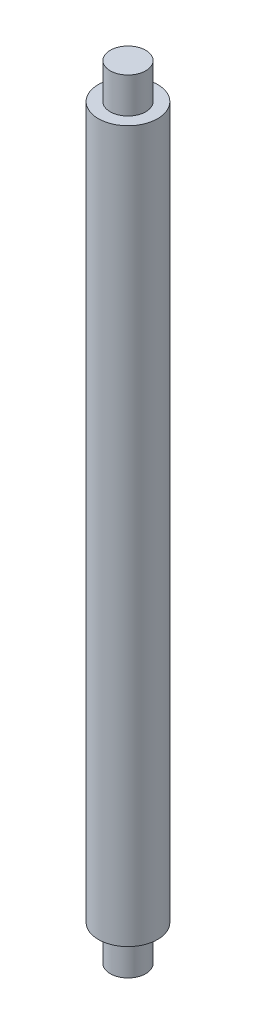
SolidWorks part; units mm, degrees
ref_plane "前视基准面" through (0, 0, 0) normal (0, 0, 1) x (1, 0, 0)
ref_plane "上视基准面" through (0, 0, 0) normal (0, 1, 0) x (1, 0, 0)
ref_plane "右视基准面" through (0, 0, 0) normal (1, 0, 0) x (0, 0, -1)
other "Configuration Table"
sketch "草图1" plane through (0, 0, 0) normal (0, 1, 0) x (1, 0, 0)
  circle A0 centre (0, 0) radius 2.5
  dimension "D1" = 5
extrude "凸台-拉伸2" add sketch "草图1" against normal mid plane 60
sketch "草图2" plane through (0, 30, 0) normal (0, 1, 0) x (1, 0, 0)
  circle A0 centre (0, 0) radius 1.5
  dimension "D1" = 3
extrude "凸台-拉伸3" add sketch "草图2" along normal blind 3
sketch "草图3" plane through (0, -30, 0) normal (0, -1, 0) x (1, 0, 0)
  circle A0 centre (0, 0) radius 1.5
  dimension "D1" = 3
extrude "凸台-拉伸4" add sketch "草图3" along normal blind 3
